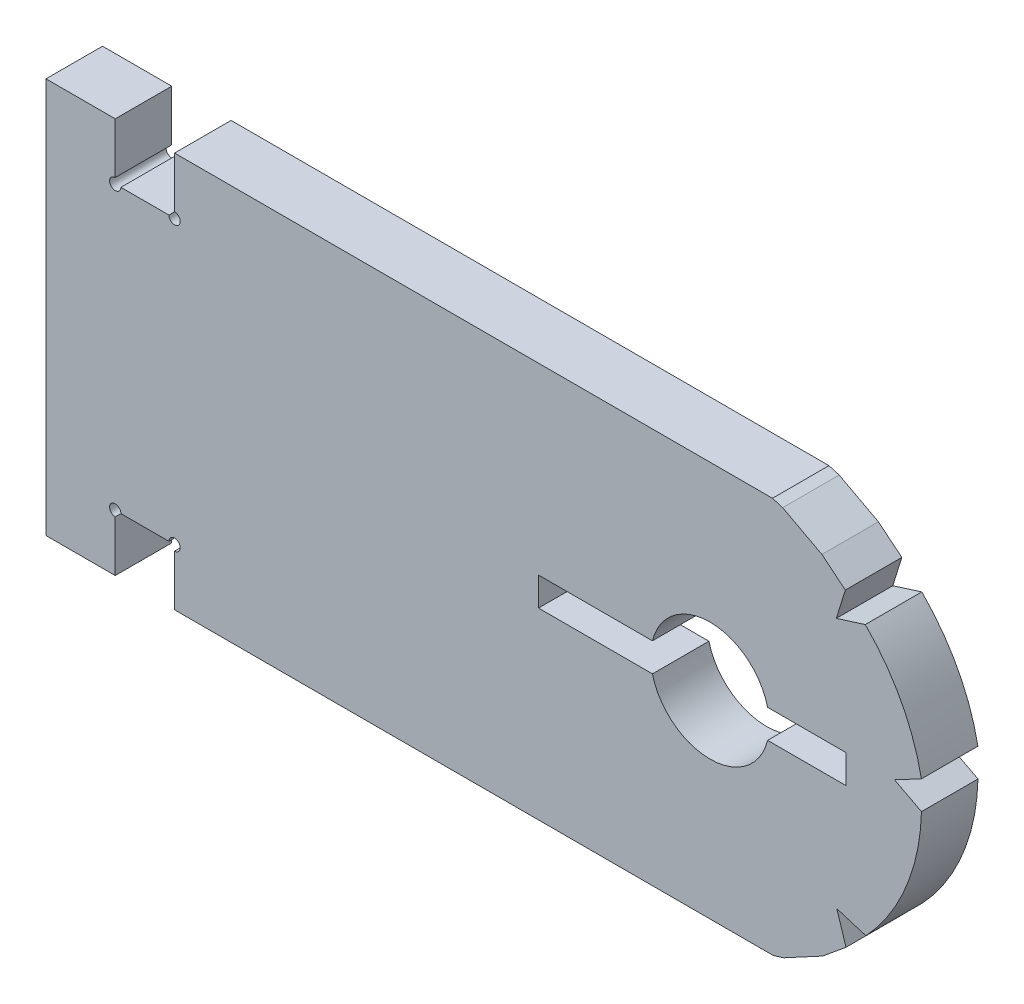
SolidWorks part; units mm, degrees
ref_plane "前视基准面" through (0, 0, 0) normal (0, 0, 1) x (1, 0, 0)
ref_plane "上视基准面" through (0, 0, 0) normal (0, 1, 0) x (1, 0, 0)
ref_plane "右视基准面" through (0, 0, 0) normal (1, 0, 0) x (0, 0, -1)
sketch "草图1" plane through (0, 0, 0) normal (0, 0, 1) x (1, 0, 0)
  line L0 (8.4619, 0.5061) -> (4.4305, 0.5061)
  line L1 (4.4305, 0.5061) -> (4.4305, -0.5061)
  line L2 (4.4305, -0.5061) -> (8.4619, -0.5061)
  line L3 (12.5381, -0.5061) -> (15.3132, -0.5061)
  line L4 (15.3132, -0.5061) -> (15.3132, 0.5061)
  line L5 (15.3132, 0.5061) -> (12.5381, 0.5061)
  line L6 (-8.45, -5.2) -> (-8.45, -7)
  line L7 (-10.35, -5) -> (-8.65, -5)
  line L8 (-10.55, -7) -> (-10.55, -5.2)
  line L9 (-13, -7) -> (-10.55, -7)
  line L10 (-13, 7) -> (-13, -7)
  line L11 (-10.55, 7) -> (-13, 7)
  line L12 (-10.55, 5.2) -> (-10.55, 7)
  line L13 (-8.65, 5) -> (-10.35, 5)
  line L14 (-8.45, 7) -> (-8.45, 5.2)
  line L15 (12.7106, 7) -> (-8.45, 7)
  line L16 (13.071, 6.8916) -> (12.7106, 7)
  line L17 (14.4593, 6.1534) -> (13.071, 6.8916)
  line L18 (15.2888, 5.4758) -> (14.4593, 6.1534)
  line L19 (14.9696, 4.4481) -> (15.2888, 5.4758)
  line L20 (15.9959, 4.7718) -> (14.9696, 4.4481)
  line L21 (17.0297, 0.5314) -> (17.9815, 1.0354)
  line L22 (17.9843, 0.0328) -> (17.0297, 0.5314)
  line L23 (14.9879, -4.4369) -> (16.0157, -4.7555)
  line L24 (15.3121, -5.4629) -> (14.9879, -4.4369)
  line L25 (14.4861, -6.1447) -> (15.3121, -5.4629)
  line L26 (13.1015, -6.8898) -> (14.4861, -6.1447)
  line L27 (12.7416, -7) -> (13.1015, -6.8898)
  line L28 (-8.45, -7) -> (12.7416, -7)
  line L29 (0, 0) -> (-13, 0) construction
  line L30 (-9.5, 0) -> (-9.5, 5) construction
  arc A1 (-8.45, -5.2) -> (-8.65, -5) centre (-8.45, -5) ccw
  arc A2 (-10.35, -5) -> (-10.55, -5.2) centre (-10.55, -5) ccw
  arc A3 (-10.55, 5.2) -> (-10.35, 5) centre (-10.55, 5) ccw
  arc A4 (-8.65, 5) -> (-8.45, 5.2) centre (-8.45, 5) ccw
  arc A5 (17.9815, 1.0354) -> (15.9959, 4.7718) centre (10.853, -0.357) ccw
  arc A6 (16.0157, -4.7555) -> (17.9843, 0.0328) centre (10.7235, 0.2191) ccw
  arc A7 (12.5381, 0.5061) -> (8.4619, 0.5061) centre (10.5, 0) ccw
  arc A8 (8.4619, -0.5061) -> (12.5381, -0.5061) centre (10.5, 0) ccw
  dimension "D4" = 0.2
  dimension "D5" = 10
  dimension "D6" = 2.1
  dimension "D1" = 9.5
  dimension "D2" = 20
  dimension "D3" = 2
  dimension "D7" = 2.1
  dimension "D8" = 13
extrude "凸台-拉伸1" add sketch "草图1" along normal blind 2
